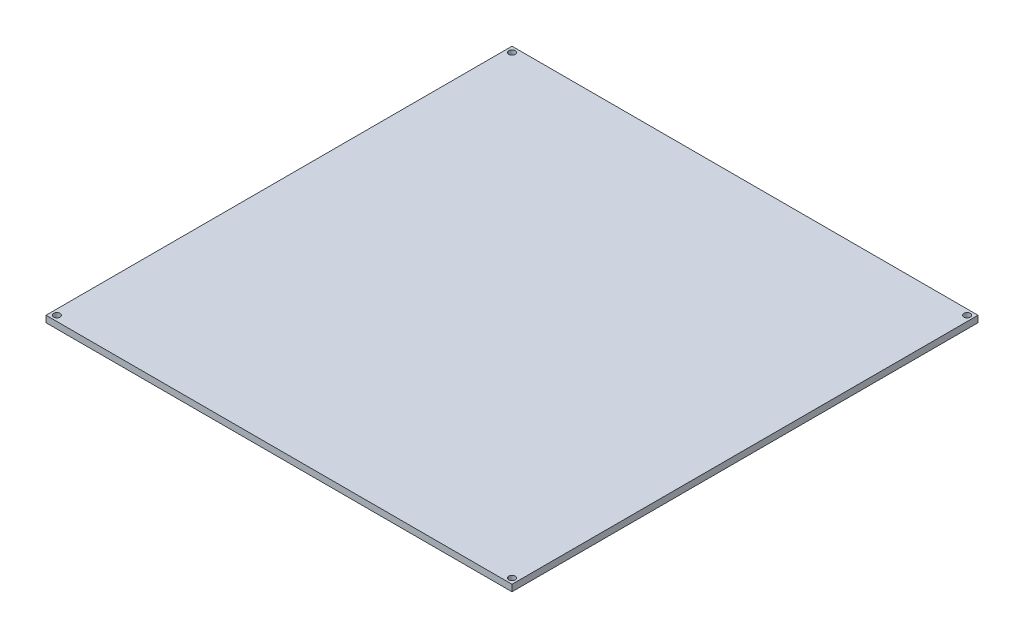
SolidWorks part; units mm, degrees
ref_plane "Front Plane" through (0, 0, 0) normal (0, 0, 1) x (1, 0, 0)
ref_plane "Top Plane" through (0, 0, 0) normal (0, 1, 0) x (1, 0, 0)
ref_plane "Right Plane" through (0, 0, 0) normal (1, 0, 0) x (0, 0, -1)
sketch "Sketch1" plane through (0, 0, 0) normal (0, 1, 0) x (1, 0, 0)
  line L0 (-107, 0) -> (107, 0) construction
  line L1 (-107, -107) -> (107, -107)
  line L2 (-107, -107) -> (-107, 107)
  line L3 (-107, 107) -> (107, 107)
  line L4 (107, -107) -> (107, 107)
  line L5 (-107, -107) -> (107, 107) construction
  line L6 (-107, 107) -> (107, -107) construction
  circle A0 centre (-104.5, 104.5) radius 1.5
  circle A1 centre (104.5, 104.5) radius 1.5
  circle A2 centre (104.5, -104.5) radius 1.5
  circle A3 centre (-104.5, -104.5) radius 1.5
  point P0 (0, 0)
  dimension "D3" = 3
  dimension "D1" = 214
  dimension "D2" = 209
extrude "Boss-Extrude1" add sketch "Sketch1" along normal blind 3
